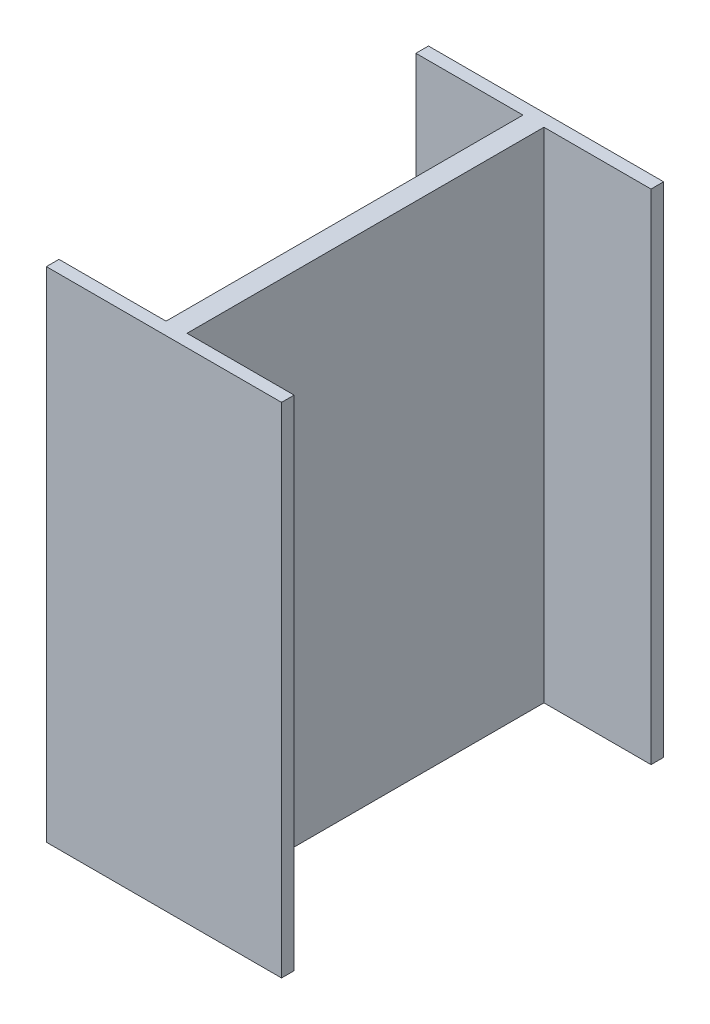
SolidWorks part; units mm, degrees
material "7075-T6 (SN)"
ref_plane "Front Plane" through (0, 0, 0) normal (0, 0, 1) x (1, 0, 0)
ref_plane "Top Plane" through (0, 0, 0) normal (0, 1, 0) x (1, 0, 0)
ref_plane "Right Plane" through (0, 0, 0) normal (1, 0, 0) x (0, 0, -1)
sketch "Sketch1" plane through (0, 0, 0) normal (0, 1, 0) x (1, 0, 0)
  line L0 (-55, 0) -> (55, 0) construction
  line L1 (560.0298, 0) -> (280.0149, 485)
  line L2 (280.0149, 485) -> (-280.0149, 485)
  line L3 (-280.0149, 485) -> (-560.0298, 0)
  line L4 (-560.0298, 0) -> (-280.0149, -485)
  line L5 (-280.0149, -485) -> (280.0149, -485)
  line L6 (280.0149, -485) -> (560.0298, 0)
  line L7 (-37.5, 455) -> (37.5, 455)
  line L8 (-25, 425) -> (-25, -425)
  line L9 (-37.5, -455) -> (37.5, -455)
  line L10 (25, 425) -> (25, -425)
  line L11 (-37.5, 455) -> (37.5, -455) construction
  line L12 (-37.5, -455) -> (37.5, 455) construction
  line L13 (37.5, 455) -> (280.0149, 455)
  line L15 (25, 425) -> (280.0149, 425)
  line L16 (280.0149, 455) -> (280.0149, 425)
  line L17 (280.0149, -455) -> (280.0149, -425)
  line L18 (37.5, -455) -> (280.0149, -455)
  line L19 (25, -425) -> (280.0149, -425)
  line L20 (0, -55) -> (0, 55) construction
  line L21 (-280.0149, -455) -> (-280.0149, -425)
  line L22 (-37.5, -455) -> (-280.0149, -455)
  line L23 (-25, -425) -> (-280.0149, -425)
  line L24 (-280.0149, 455) -> (-280.0149, 425)
  line L25 (-37.5, 455) -> (-280.0149, 455)
  line L26 (-25, 425) -> (-280.0149, 425)
  circle A0 centre (0, 0) radius 485 construction
  dimension "D1" = 970
  dimension "D2" = 75
  dimension "D3" = 30
  dimension "D4" = 30
  dimension "D5" = 50
extrude "Boss-Extrude2" add sketch "Sketch1" along normal blind 1187.25 contours L8 L23 L21 L22 L9 L18 L17 L19 L10 L15 L16 L13 L7 L25 L24 L26
